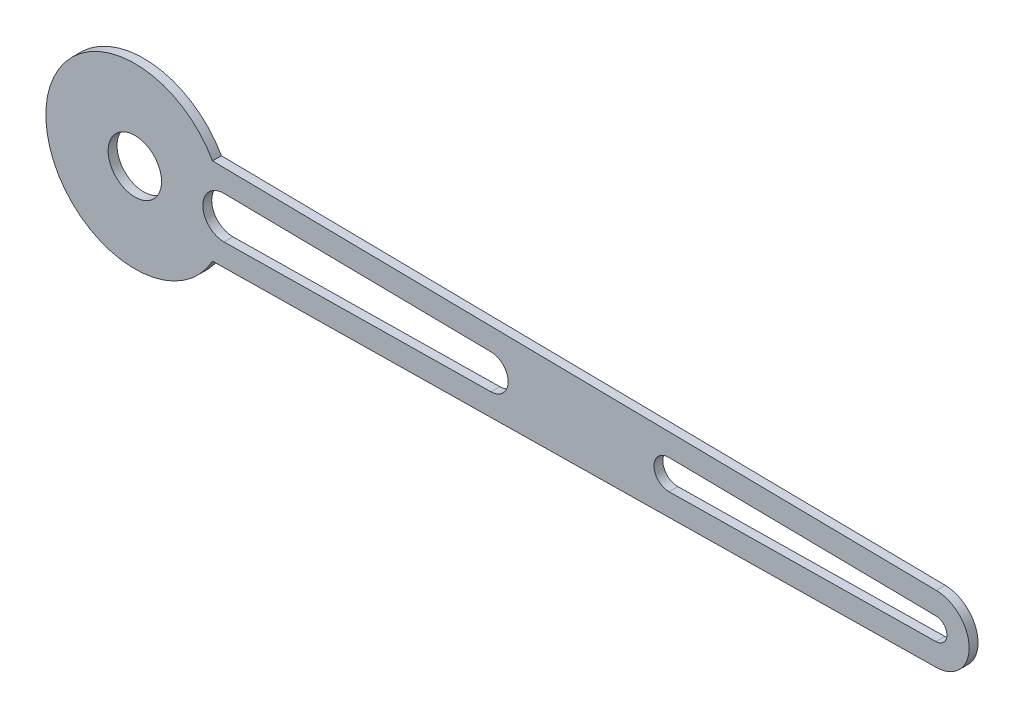
SolidWorks part; units mm, degrees
material "PW110:Mi:0:2:C1:0:1:2:Re:26:"
ref_plane "Front" through (0, 0, 0) normal (0, 0, 1) x (1, 0, 0)
ref_plane "Top" through (0, 0, 0) normal (0, 1, 0) x (1, 0, 0)
ref_plane "Right" through (0, 0, 0) normal (1, 0, 0) x (0, 0, -1)
sketch "Sketch1" plane through (0, 0, 0) normal (0, 0, 1) x (1, 0, 0)
  line L0 (-19.6851, 0) -> (20.2961, 0) construction
  line L1 (0, 17.3189) -> (0, -16.8635) construction
  circle A0 centre (10, 0) radius 1.75 construction
  circle A1 centre (-7.5, 0) radius 4 construction
  circle A2 centre (0, 7.5) radius 4 construction
  circle A3 centre (0, -7.5) radius 4 construction
  point P12 (0, 0)
  dimension "D1" = 8
  dimension "D2" = 8
  dimension "D3" = 8
  dimension "D4" = 3.5
  dimension "D5" = 10
  dimension "D6" = 7.5
  dimension "D7" = 7.5
  dimension "D8" = 7.5
sketch "Sketch3" plane through (0, 0, 0) normal (0, 0, 1) x (1, 0, 0)
  line L1 (0.3749, 13.0072) -> (0.6099, 0.7925) construction
  line L2 (-0.3749, 13.0072) -> (-0.6099, 0.7925) construction
  line L3 (0.125, 13.0024) -> (0.2211, 8.0043) construction
  line L4 (-0.125, 13.0024) -> (-0.2211, 8.0043) construction
  line L5 (-0.2788, 5.0054) -> (-0.3557, 1.0068) construction
  line L6 (0.2788, 5.0054) -> (0.3557, 1.0068) construction
  arc A0 (-0.3557, 1.0068) -> (0.3557, 1.0068) centre (0, 1) ccw construction
  arc A1 (0.3749, 13.0072) -> (-0.3749, 13.0072) centre (0, 13) ccw construction
  arc A2 (-0.6099, 0.7925) -> (0.6099, 0.7925) centre (0, 0) ccw construction
  circle A3 centre (0, 0) radius 0.5 construction
  arc A4 (0.125, 13.0024) -> (-0.125, 13.0024) centre (0, 13) ccw construction
  arc A5 (0.2788, 5.0054) -> (-0.2788, 5.0054) centre (0, 5) ccw construction
  arc A6 (-0.2211, 8.0043) -> (0.2211, 8.0043) centre (0, 8) ccw construction
  dimension "D4" = 0.25
sketch "Sketch4" plane through (0, 0, 0) normal (0, 0, 1) x (1, 0, 0)
  line L0 (-19.6851, 0) -> (20.2961, 0) construction
  line L1 (0.8729, 0.4879) -> (9.0052, 0.375)
  line L2 (0.8729, -0.4879) -> (9.0052, -0.375)
  line L3 (1.0033, 0.2361) -> (4.0027, 0.1944)
  line L4 (1.0033, -0.2361) -> (4.0027, -0.1944)
  line L5 (6.0023, -0.1667) -> (9.0017, -0.125)
  line L6 (6.0023, 0.1667) -> (9.0017, 0.125)
  arc A2 (9.0017, -0.125) -> (9.0017, 0.125) centre (9, 0) ccw
  arc A3 (0.8729, 0.4879) -> (0.8729, -0.4879) centre (0, 0) ccw
  arc A4 (4.0027, -0.1944) -> (4.0027, 0.1944) centre (4, 0) ccw
  arc A5 (9.0052, -0.375) -> (9.0052, 0.375) centre (9, 0) ccw
  arc A7 (1.0033, 0.2361) -> (1.0033, -0.2361) centre (1, 0) ccw
  arc A8 (6.0023, 0.1667) -> (6.0023, -0.1667) centre (6, 0) ccw
  circle A9 centre (0, 0) radius 0.3
  dimension "D1" = 9
  dimension "D2" = 3
  dimension "D3" = 0.75
  dimension "D4" = 0.25
  dimension "D5" = 4
  dimension "D6" = 3
extrude "Base-Extrude" add sketch "Sketch4" along normal blind 0.1
